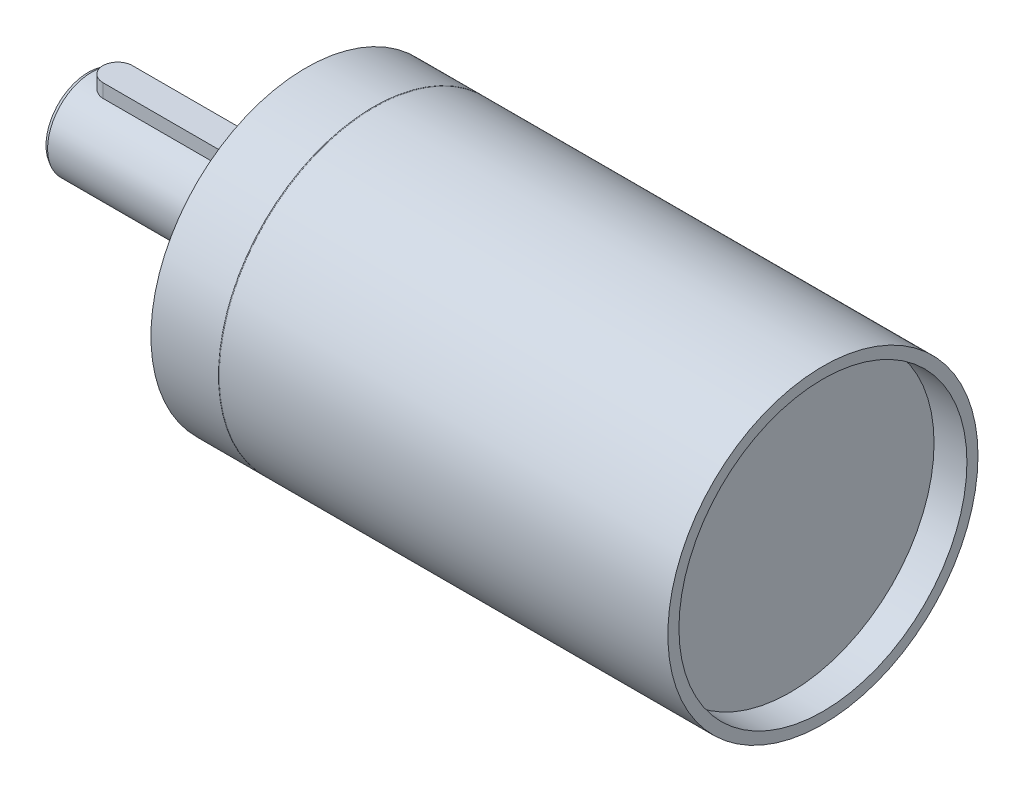
SolidWorks part; units mm, degrees
ref_plane "Front Plane" through (0, 0, 0) normal (0, 0, 1) x (1, 0, 0)
ref_plane "Top Plane" through (0, 0, 0) normal (0, 1, 0) x (1, 0, 0)
ref_plane "Right Plane" through (0, 0, 0) normal (1, 0, 0) x (0, 0, -1)
sketch "Sketch1" plane through (0, 0, 0) normal (0, 0, 1) x (1, 0, 0)
  line L0 (0, 21) -> (0, 0)
  line L1 (0, 0) -> (70, 0)
  line L2 (70, 0) -> (70, 21)
  line L3 (70, 21) -> (9.25, 21)
  line L4 (9.15, 21) -> (0, 21)
  line L5 (0, 0) -> (70, 0) construction
  arc A0 (9.25, 21) -> (9.15, 21) centre (9.2, 21.0866) cw
revolve "Revolve1" add sketch "Sketch1" angle 360 about L5
sketch "Sketch2" plane through (0, 0, 0) normal (-1, 0, 0) x (0, 0, 1)
  circle A0 centre (0, 0) radius 14
extrude "Boss-Extrude1" add sketch "Sketch2" along normal blind 3
sketch "Sketch3" plane through (-3, 0, 0) normal (-1, 0, 0) x (0, 0, 1)
  circle A0 centre (0, 0) radius 6
extrude "Boss-Extrude2" add sketch "Sketch3" along normal blind 26.5
sketch "Sketch4" plane through (-3, 0, 0) normal (-1, 0, 0) x (0, 0, 1)
  line L0 (0.2939, -7.6168) -> (0.2939, -5.9928)
  line L1 (-0.2939, -5.9928) -> (-0.2939, -7.6168)
  arc A0 (0.2939, -5.9928) -> (-0.2939, -5.9928) centre (0, 0) ccw
  arc A1 (-0.2939, -7.6168) -> (-2.8825, -5.9928) centre (0.2939, -3.8048) cw
  arc A2 (-2.8825, -5.9928) -> (2.8825, -5.9928) centre (0, 0) cw
  arc A3 (2.8825, -5.9928) -> (0.2939, -7.6168) centre (0.2939, -4.7418) cw
extrude "Boss-Extrude3" add sketch "Sketch4" along normal blind 1
ref_plane "Plane1" through (0, 7.5, 0) normal (0, 1, 0) x (1, 0, 0)
sketch "Sketch5" plane through (0, 7.5, 0) normal (0, 1, 0) x (1, 0, 0)
  line L0 (-9.5, 2) -> (-25.5, 2)
  line L1 (-25.5, -2) -> (-9.5, -2)
  arc A0 (-25.5, 2) -> (-25.5, -2) centre (-25.5, 0) ccw
  arc A1 (-9.5, -2) -> (-9.5, 2) centre (-9.5, 0) ccw
extrude "Boss-Extrude4" add sketch "Sketch5" against normal up to next
hole_wizard "M36 Clearance Hole1" positions "Sketch7" profile "Sketch6" hole size "M36" standard "ANSI Metric"
sketch "Sketch7" plane through (70, 0, 0) normal (1, 0, 0) x (0, 0, -1)
  point P0 (0, 0)
sketch "Sketch6" plane through (70, 0, 0) normal (0, 1, 0) x (0, 0, -1)
  line L0 (0, 0) -> (0, 4.45)
  line L1 (0, 4.45) -> (19.5, 4.45)
  line L2 (19.5, 4.45) -> (19.5, 0)
  line L5 (19.5, 0) -> (0, 0)
  line L10 (0, 4.45) -> (-19.5, 4.45) construction
  line L11 (0, -6.35) -> (0, 107.95) construction
  dimension "Hole Dia." = 39
  dimension "Hole Depth" = 4.45
  dimension "Drill Angle" = 180
hole_wizard "Ø1.5 (1.5) Diameter Hole1" positions "Sketch9" profile "Sketch8" hole size "Ø1.5" standard "ANSI Metric"
sketch "Sketch9" plane through (0, 0, 0) normal (-1, 0, 0) x (0, 0, 1)
  point P0 (-7.4623, 18.0157)
sketch "Sketch8" plane through (0, 18.0157, -7.4623) normal (0, 1, 0) x (0, 0, 1)
  line L0 (0, 0) -> (0, 2.4506)
  line L1 (0, 2.4506) -> (0.75, 2)
  line L2 (0.75, 2) -> (0.75, 0)
  line L5 (0.75, 0) -> (0, 0)
  line L10 (0, 2.4506) -> (-0.75, 2) construction
  line L11 (0, -6.35) -> (0, 107.95) construction
  dimension "Hole Dia." = 1.5
  dimension "Hole Depth" = 2
  dimension "Drill Angle" = 118
hole_wizard "Ø3.3 (3.3) Diameter Hole1" positions "Sketch11" profile "Sketch10" hole size "Ø3.3" standard "ANSI Metric"
sketch "Sketch11" plane through (0, 0, 0) normal (-1, 0, 0) x (0, 0, 1)
  point P0 (0, 17.5)
  point P1 (17.5, 0)
  point P2 (0, -17.5)
  point P3 (-17.5, 0)
sketch "Sketch10" plane through (0, 17.5, 0) normal (0, 1, 0) x (0, 0, 1)
  line L0 (0, 0) -> (0, 6.9914)
  line L1 (0, 6.9914) -> (1.65, 6)
  line L2 (1.65, 6) -> (1.65, 0)
  line L5 (1.65, 0) -> (0, 0)
  line L10 (0, 6.9914) -> (-1.65, 6) construction
  line L11 (0, -6.35) -> (0, 107.95) construction
  dimension "Hole Dia." = 3.3
  dimension "Hole Depth" = 6
  dimension "Drill Angle" = 118
hole_wizard "Ø1.25 (1.25) Diameter Hole1" positions "Sketch13" profile "Sketch12" hole size "Ø1.25" standard "ANSI Metric"
sketch "Sketch13" plane through (-29.5, 0, 0) normal (-1, 0, 0) x (0, 0, 1)
  point P0 (0, 0)
sketch "Sketch12" plane through (-29.5, 0, 0) normal (0, 1, 0) x (0, 0, 1)
  line L0 (0, 0) -> (0, 2.3)
  line L1 (0, 2.3) -> (0.625, 1.9392)
  line L2 (0.625, 1.9392) -> (0.625, 1.2124)
  line L3 (0.625, 1.2124) -> (1.325, 0)
  line L5 (1.325, 0) -> (0, 0)
  line L6 (-0.625, 1.2124) -> (-1.325, 0) construction
  line L10 (0, 2.3) -> (-0.625, 1.9392) construction
  line L11 (0, -6.35) -> (0, 107.95) construction
  dimension "Hole Dia." = 1.25
  dimension "Hole Depth" = 1.9392
  dimension "Near C'Sink Dia." = 2.65
  dimension "Near C'Sink Angle" = 60
  dimension "Drill Angle" = 120
chamfer "Chamfer1" distance 0.2887 angle 60 1 edges at (-29.5, 0, 6)
